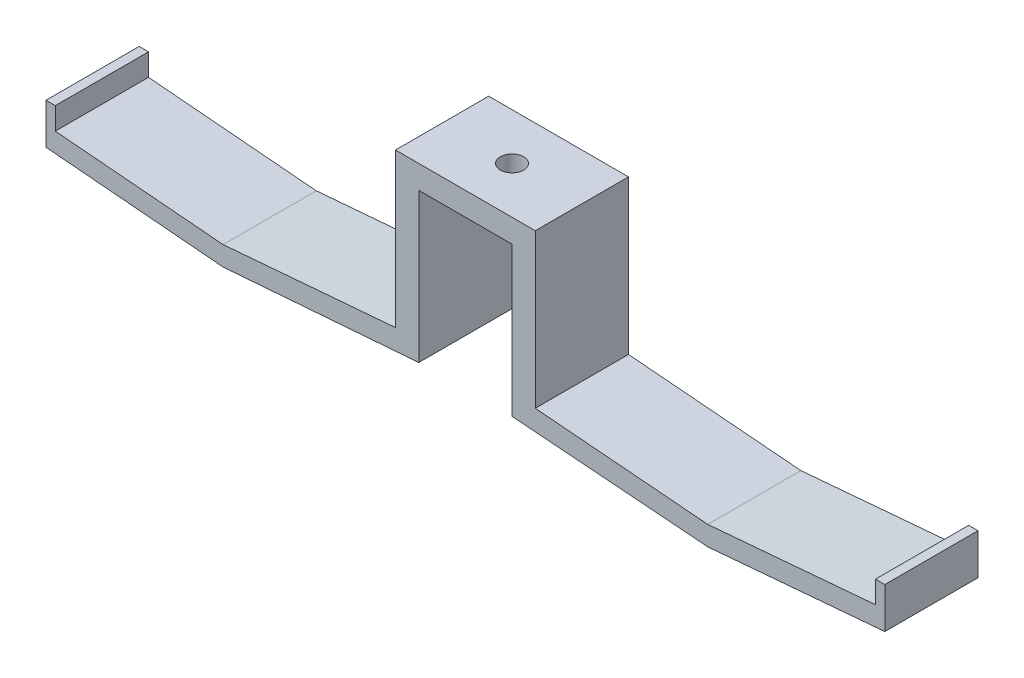
SolidWorks part; units mm, degrees
material "Nylon 6/10"
ref_plane "Front Plane" through (0, 0, 0) normal (0, 0, 1) x (1, 0, 0)
ref_plane "Top Plane" through (0, 0, 0) normal (0, 1, 0) x (1, 0, 0)
ref_plane "Right Plane" through (0, 0, 0) normal (1, 0, 0) x (0, 0, -1)
other "Center of Mass"
sketch "Sketch2" plane through (0, 0, 0) normal (0, 0, 1) x (1, 0, 0)
  line L1 (12.7, 0) -> (12.7, -40.64)
  line L2 (12.7, -40.64) -> (66.04, -44.7734)
  line L3 (66.04, -44.7734) -> (114.3, -40.64)
  line L4 (114.3, -40.64) -> (114.3, -29.5334)
  line L5 (111.76, -29.5334) -> (111.76, -35.56)
  line L6 (111.76, -35.56) -> (66.04, -39.4758)
  line L19 (114.3, -29.5334) -> (111.76, -29.5334)
  line L20 (0, 125.2351) -> (0, -75.9356) construction
  line L21 (12.7, 0) -> (-12.7, 0)
  line L22 (0, 0) -> (0, 6.35)
  line L23 (19.05, 6.35) -> (-19.05, 6.35)
  line L24 (19.05, 6.35) -> (19.05, 0)
  line L25 (19.05, 0) -> (19.05, -35.56)
  line L26 (19.05, -35.56) -> (66.04, -39.4758)
  line L27 (-19.05, 0) -> (-19.05, -35.56)
  line L28 (-19.05, 6.35) -> (-19.05, 0)
  line L29 (-12.7, 0) -> (-12.7, -40.64)
  line L30 (-12.7, -40.64) -> (-66.04, -44.7734)
  line L31 (-66.04, -44.7734) -> (-114.3, -40.64)
  line L32 (-114.3, -40.64) -> (-114.3, -29.5334)
  line L33 (-114.3, -29.5334) -> (-111.76, -29.5334)
  line L34 (-111.76, -29.5334) -> (-111.76, -35.56)
  line L35 (-111.76, -35.56) -> (-66.04, -39.4758)
  line L36 (-19.05, -35.56) -> (-66.04, -39.4758)
  dimension "D1" = 19.05
  dimension "D2" = 12.7
  dimension "D3" = 35.56
  dimension "D4" = 3.9158
  dimension "D5" = 40.64
  dimension "D6" = 2.54
  dimension "D7" = 45.72
  dimension "D8" = 46.99
  dimension "D9" = 15.24
  dimension "D10" = 6.35
extrude "Boss-Extrude1" add sketch "Sketch2" along normal blind 25.4 contours L26 L25 L24 L23 L22 L21 L1 L2 L3 L4 L19 L5 L6 | L27 L36 L35 L34 L33 L32 L31 L30 L29 L21 L22 L23 L28
sketch "Sketch3" plane through (0, 6.35, 0) normal (0, 1, 0) x (1, 0, 0)
  line L0 (19.05, -12.7) -> (-19.05, -12.7) construction
  line L1 (19.05, -25.4) -> (19.05, 0) construction
  line L2 (-19.05, -25.4) -> (-19.05, 0) construction
  circle A0 centre (0, -12.7) radius 3.175
  dimension "D1" = 6.35
extrude "Cut-Extrude1" cut sketch "Sketch3" against normal up to next
